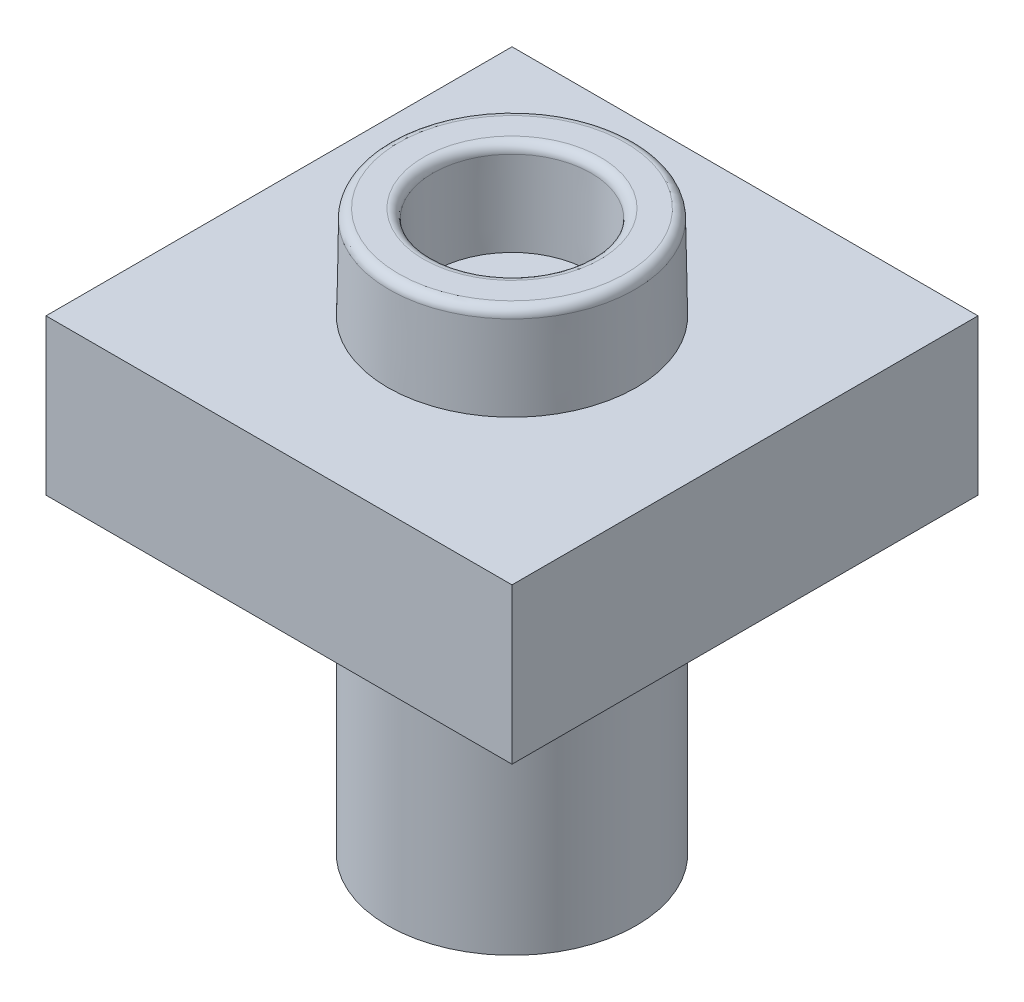
SolidWorks part; units mm, degrees
ref_plane "Front Plane" through (0, 0, 0) normal (0, 0, 1) x (1, 0, 0)
ref_plane "Top Plane" through (0, 0, 0) normal (0, 1, 0) x (1, 0, 0)
ref_plane "Right Plane" through (0, 0, 0) normal (1, 0, 0) x (0, 0, -1)
sketch "Sketch1" plane through (0, 0, 0) normal (0, 1, 0) x (1, 0, 0)
  line L1 (7.5, -7.5) -> (-7.5, -7.5)
  line L2 (7.5, -7.5) -> (7.5, 7.5)
  line L3 (7.5, 7.5) -> (-7.5, 7.5)
  line L4 (-7.5, -7.5) -> (-7.5, 7.5)
  line L5 (7.5, -7.5) -> (-7.5, 7.5) construction
  line L6 (7.5, 7.5) -> (-7.5, -7.5) construction
  point P0 (0, 0)
  dimension "D1" = 15
  dimension "D2" = 15
extrude "Boss-Extrude1" add sketch "Sketch1" along normal blind 5
sketch "Sketch2" plane through (0, 5, 0) normal (0, 1, 0) x (1, 0, 0)
  circle A0 centre (0, 0) radius 4
  circle A1 centre (0, 0) radius 2.5
  dimension "D1" = 8
  dimension "D2" = 5
extrude "Boss-Extrude2" add sketch "Sketch2" along normal blind 3 draft 1
fillet "Fillet1" radius 0.3 2 edges at (0, 8, 2.5524) (0, 8, 3.9476)
sketch "Sketch3" plane through (0, 0, 0) normal (0, -1, 0) x (1, 0, 0)
  circle A0 centre (0, 0) radius 4
  dimension "D1" = 8
extrude "Boss-Extrude3" add sketch "Sketch3" along normal blind 10
